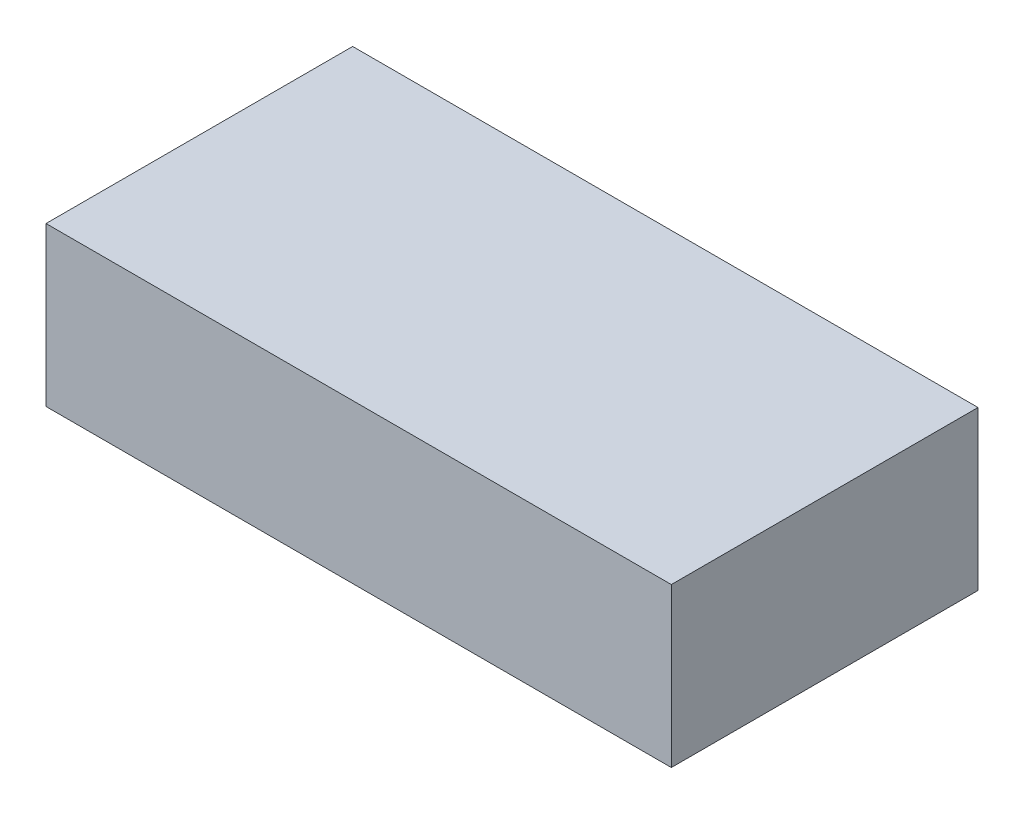
SolidWorks part; units mm, degrees
ref_plane "Front Plane" through (0, 0, 0) normal (0, 0, 1) x (1, 0, 0)
ref_plane "Top Plane" through (0, 0, 0) normal (0, 1, 0) x (1, 0, 0)
ref_plane "Right Plane" through (0, 0, 0) normal (1, 0, 0) x (0, 0, -1)
sketch "Sketch2" plane through (0, 0, 0) normal (0, 1, 0) x (1, 0, 0)
  line L1 (-59.1844, 29.0243) -> (59.1844, 29.0243)
  line L2 (-59.1844, 29.0243) -> (-59.1844, -29.0243)
  line L3 (-59.1844, -29.0243) -> (59.1844, -29.0243)
  line L4 (59.1844, 29.0243) -> (59.1844, -29.0243)
  point P4 (-59.1844, 0)
  point P6 (0, 29.0243)
  point P7 (59.1844, 0)
  point P8 (0, -29.0243)
extrude "Boss-Extrude1" add sketch "Sketch2" along normal blind 30
sketch "Sketch3" plane through (0, 30, 0) normal (0, 1, 0) x (1, 0, 0)
  line L1 (-16.2196, 16.0838) -> (53.7804, 16.0838)
  line L2 (-16.2196, 16.0838) -> (-16.2196, -13.9162)
  line L3 (-16.2196, -13.9162) -> (53.7804, -13.9162)
  line L4 (53.7804, 16.0838) -> (53.7804, -13.9162)
